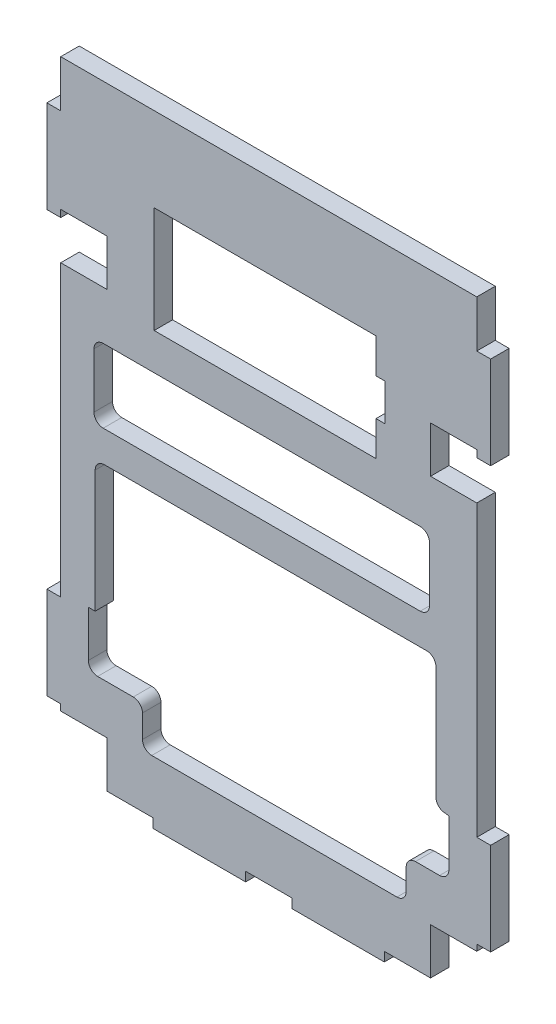
SolidWorks part; units mm, degrees
ref_plane "前视基准面" through (0, 0, 0) normal (0, 0, 1) x (1, 0, 0)
ref_plane "上视基准面" through (0, 0, 0) normal (0, 1, 0) x (1, 0, 0)
ref_plane "右视基准面" through (0, 0, 0) normal (1, 0, 0) x (0, 0, -1)
sketch "Model" plane through (0, 0, 0) normal (0, 0, 1) x (1, 0, 0)
  line L0 (1417.5795, 528.7776) -> (1417.5795, 523.704)
  line L1 (1417.5795, 514.4742) -> (1417.5795, 513.704)
  line L2 (1417.5795, 509.4742) -> (1417.5795, 478.1551)
  line L3 (1417.5795, 468.1551) -> (1417.5795, 467.4742)
  line L4 (1417.5795, 478.1551) -> (1419.0795, 478.1551)
  line L5 (1417.5795, 468.1551) -> (1419.0795, 468.1551)
  line L6 (1417.5795, 523.704) -> (1419.0795, 523.704)
  line L7 (1417.5795, 513.704) -> (1419.0795, 513.704)
  line L8 (1417.5795, 467.4742) -> (1412.5795, 467.4742)
  line L9 (1412.5795, 467.4742) -> (1412.5795, 462.4742)
  line L10 (1417.5795, 514.4742) -> (1412.5795, 514.4742)
  line L11 (1412.5795, 514.4742) -> (1412.5795, 509.4742)
  line L12 (1412.5795, 509.4742) -> (1417.5795, 509.4742)
  line L13 (1419.0795, 523.704) -> (1419.0795, 513.704)
  line L14 (1419.0795, 478.1551) -> (1419.0795, 468.1551)
  line L15 (1372.5795, 528.7776) -> (1417.5795, 528.7776)
  line L16 (1392.5795, 462.4742) -> (1397.5795, 462.4742)
  line L17 (1407.5795, 462.4742) -> (1412.5795, 462.4742)
  line L18 (1397.5795, 461.4742) -> (1407.5795, 461.4742)
  line L19 (1407.5795, 462.4742) -> (1407.5795, 461.4742)
  line L20 (1397.5795, 461.4742) -> (1397.5795, 462.4742)
  line L21 (1372.5795, 514.4742) -> (1372.5795, 513.704)
  line L22 (1372.5795, 509.4742) -> (1372.5795, 478.1551)
  line L23 (1372.5795, 468.1551) -> (1372.5795, 467.4742)
  line L24 (1372.5795, 528.7776) -> (1372.5795, 523.704)
  line L25 (1372.5795, 478.1551) -> (1371.0795, 478.1551)
  line L26 (1372.5795, 468.1551) -> (1371.0795, 468.1551)
  line L27 (1372.5795, 523.704) -> (1371.0795, 523.704)
  line L28 (1372.5795, 513.704) -> (1371.0795, 513.704)
  line L29 (1372.5795, 467.4742) -> (1377.5795, 467.4742)
  line L30 (1377.5795, 467.4742) -> (1377.5795, 462.4742)
  line L31 (1372.5795, 514.4742) -> (1377.5795, 514.4742)
  line L32 (1377.5795, 514.4742) -> (1377.5795, 509.4742)
  line L33 (1377.5795, 509.4742) -> (1372.5795, 509.4742)
  line L34 (1371.0795, 523.704) -> (1371.0795, 513.704)
  line L35 (1371.0795, 478.1551) -> (1371.0795, 468.1551)
  line L36 (1382.5795, 462.4742) -> (1377.5795, 462.4742)
  line L37 (1392.5795, 461.4742) -> (1382.5795, 461.4742)
  line L38 (1382.5795, 462.4742) -> (1382.5795, 461.4742)
  line L39 (1392.5795, 461.4742) -> (1392.5795, 462.4742)
  line L40 (1413.1645, 491.9178) -> (1413.1645, 479.7065)
  line L41 (1413.5552, 472.5675) -> (1410.9472, 472.5675)
  line L42 (1409.9472, 471.5675) -> (1409.9472, 469.2397)
  line L43 (1408.9472, 468.2397) -> (1382.4204, 468.2397)
  line L44 (1381.4204, 469.2397) -> (1381.4204, 471.7211)
  line L45 (1380.4204, 472.7211) -> (1376.5698, 472.7211)
  line L46 (1375.5698, 478.6995) -> (1376.3051, 478.6995)
  line L47 (1376.3051, 478.6995) -> (1376.3051, 491.9178)
  line L48 (1414.5552, 473.5675) -> (1414.5552, 478.6544)
  line L49 (1375.5698, 473.7211) -> (1375.5698, 478.6995)
  line L50 (1414.5552, 478.6544) -> (1414.1645, 478.7065)
  line L51 (1412.1645, 492.9178) -> (1377.3051, 492.9178)
  line L52 (1382.6795, 519.6772) -> (1406.6795, 519.6772)
  line L53 (1406.6795, 519.6772) -> (1406.6795, 515.9272)
  line L54 (1406.6795, 511.9272) -> (1406.6795, 508.1772)
  line L55 (1406.6795, 508.1772) -> (1382.6795, 508.1772)
  line L56 (1382.6795, 508.1772) -> (1382.6795, 519.6772)
  line L57 (1411.462, 504.2169) -> (1377.1752, 504.2169)
  line L58 (1376.1752, 503.2169) -> (1376.1752, 497.2767)
  line L59 (1377.1752, 496.2767) -> (1411.462, 496.2767)
  line L60 (1412.462, 497.2767) -> (1412.462, 503.2169)
  line L61 (1406.6795, 511.9272) -> (1407.6795, 511.9272)
  line L62 (1407.6795, 511.9272) -> (1407.6795, 515.9272)
  line L63 (1407.6795, 515.9272) -> (1406.6795, 515.9272)
  arc A0 (1413.1645, 479.7065) -> (1414.1645, 478.7065) centre (1414.1645, 479.7065) ccw
  arc A1 (1413.5552, 472.5675) -> (1414.5552, 473.5675) centre (1413.5552, 473.5675) ccw
  arc A2 (1410.9472, 472.5675) -> (1409.9472, 471.5675) centre (1410.9472, 471.5675) ccw
  arc A3 (1408.9472, 468.2397) -> (1409.9472, 469.2397) centre (1408.9472, 469.2397) ccw
  arc A4 (1381.4204, 469.2397) -> (1382.4204, 468.2397) centre (1382.4204, 469.2397) ccw
  arc A5 (1381.4204, 471.7211) -> (1380.4204, 472.7211) centre (1380.4204, 471.7211) ccw
  arc A6 (1375.5698, 473.7211) -> (1376.5698, 472.7211) centre (1376.5698, 473.7211) ccw
  arc A7 (1377.3051, 492.9178) -> (1376.3051, 491.9178) centre (1377.3051, 491.9178) ccw
  arc A8 (1413.1645, 491.9178) -> (1412.1645, 492.9178) centre (1412.1645, 491.9178) ccw
  arc A9 (1412.462, 503.2169) -> (1411.462, 504.2169) centre (1411.462, 503.2169) ccw
  arc A10 (1377.1752, 504.2169) -> (1376.1752, 503.2169) centre (1377.1752, 503.2169) ccw
  arc A11 (1376.1752, 497.2767) -> (1377.1752, 496.2767) centre (1377.1752, 497.2767) ccw
  arc A12 (1411.462, 496.2767) -> (1412.462, 497.2767) centre (1411.462, 497.2767) ccw
extrude "凸台-拉伸1" add sketch "Model" along normal blind 2
